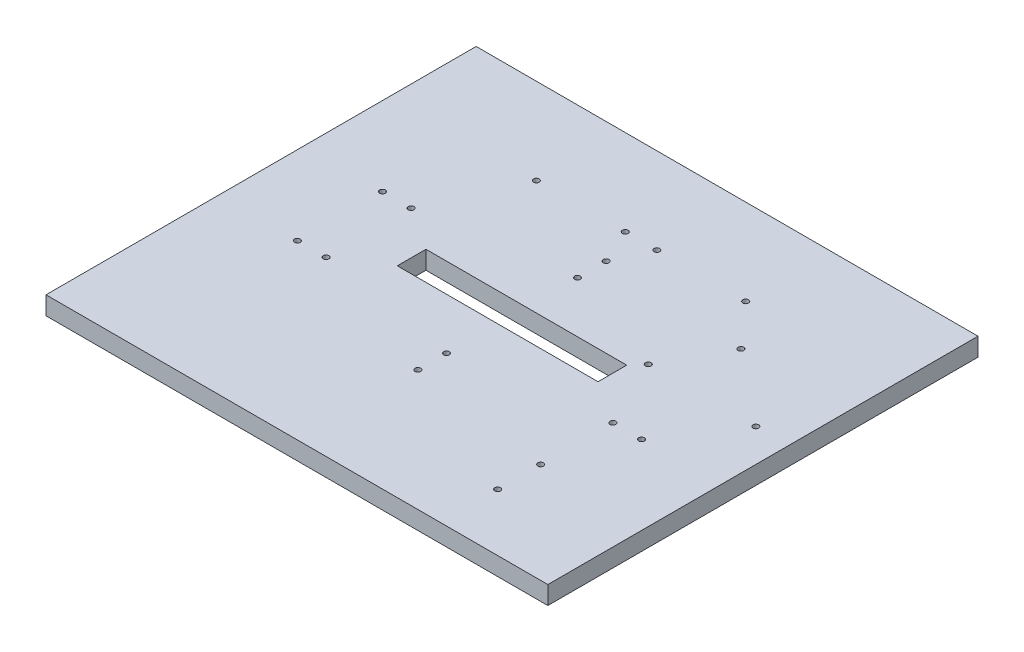
SolidWorks part; units mm, degrees
ref_plane "Front Plane" through (0, 0, 0) normal (0, 0, 1) x (1, 0, 0)
ref_plane "Top Plane" through (0, 0, 0) normal (0, 1, 0) x (1, 0, 0)
ref_plane "Right Plane" through (0, 0, 0) normal (1, 0, 0) x (0, 0, -1)
sketch "Sketch1" plane through (0, 0, 0) normal (0, 1, 0) x (1, 0, 0)
  line L0 (0, 150) -> (350, 150) construction
  line L1 (0, 0) -> (350, 0)
  line L3 (0, 300) -> (350, 300)
  line L4 (350, 0) -> (350, 300)
  line L5 (102, 240) -> (248, 240) construction
  line L6 (245, 140) -> (105, 140)
  line L7 (245, 140) -> (245, 160)
  line L8 (245, 160) -> (105, 160)
  line L9 (105, 140) -> (105, 160)
  line L10 (245, 140) -> (105, 160) construction
  line L11 (245, 160) -> (105, 140) construction
  line L12 (175, 240) -> (175, 160) construction
  line L13 (275, 70) -> (275, 40) construction
  line L14 (0, 300) -> (0, 0)
  line L15 (75, 120.35) -> (275, 120.35) construction
  line L16 (175, 104.35) -> (175, 195.65) construction
  line L17 (252.0554, 168) -> (327.0554, 168) construction
  line L18 (75, 179.65) -> (275, 179.65) construction
  circle A0 centre (102, 240) radius 2
  circle A2 centre (248, 240) radius 2
  circle A3 centre (275, 70) radius 2
  circle A4 centre (275, 40) radius 2
  circle A5 centre (186, 240) radius 2
  circle A6 centre (164, 240) radius 2
  circle A9 centre (175, 195.65) radius 2
  circle A10 centre (175, 215.65) radius 2
  circle A11 centre (175, 104.35) radius 2
  circle A12 centre (175, 84.35) radius 2
  circle A15 centre (252.0554, 168) radius 2
  circle A16 centre (327.0554, 168) radius 2
  circle A17 centre (75, 120.35) radius 2
  circle A18 centre (55, 120.35) radius 2
  circle A19 centre (275, 120.35) radius 2
  circle A20 centre (295, 120.35) radius 2
  circle A21 centre (75, 179.65) radius 2
  circle A22 centre (55, 179.65) radius 2
  circle A23 centre (275, 209.65) radius 2
  point P7 (175, 150)
  point P28 (175, 120.35)
  point P44 (175, 150)
  point P50 (175, 179.65)
  dimension "D5" = 4
  dimension "D6" = 4
  dimension "D9" = 4
  dimension "D10" = 4
  dimension "D14" = 4
  dimension "D15" = 4
  dimension "D18" = 4
  dimension "D19" = 4
  dimension "D20" = 16
  dimension "D21" = 200
  dimension "D22" = 4
  dimension "D23" = 4
  dimension "D24" = 4
  dimension "D25" = 4
  dimension "D33" = 4
  dimension "D34" = 4
  dimension "D28" = 4
  dimension "D30" = 4
  dimension "D39" = 4
  dimension "D40" = 4
  dimension "D42" = 4
  dimension "D1" = 300
  dimension "D2" = 350
  dimension "D3" = 20
  dimension "D4" = 140
  dimension "D7" = 146
  dimension "D8" = 80
  dimension "D11" = 30
  dimension "D12" = 70
  dimension "D13" = 30
  dimension "D16" = 62
  dimension "D17" = 62
  dimension "D26" = 20
  dimension "D27" = 20
  dimension "D29" = 20
  dimension "D31" = 20
  dimension "D32" = 91.3
  dimension "D35" = 75
  dimension "D36" = 8
  dimension "D37" = 16
  dimension "D38" = 200
  dimension "D41" = 20
  dimension "D43" = 30
extrude "Boss-Extrude1" add sketch "Sketch1" along normal blind 12.7
